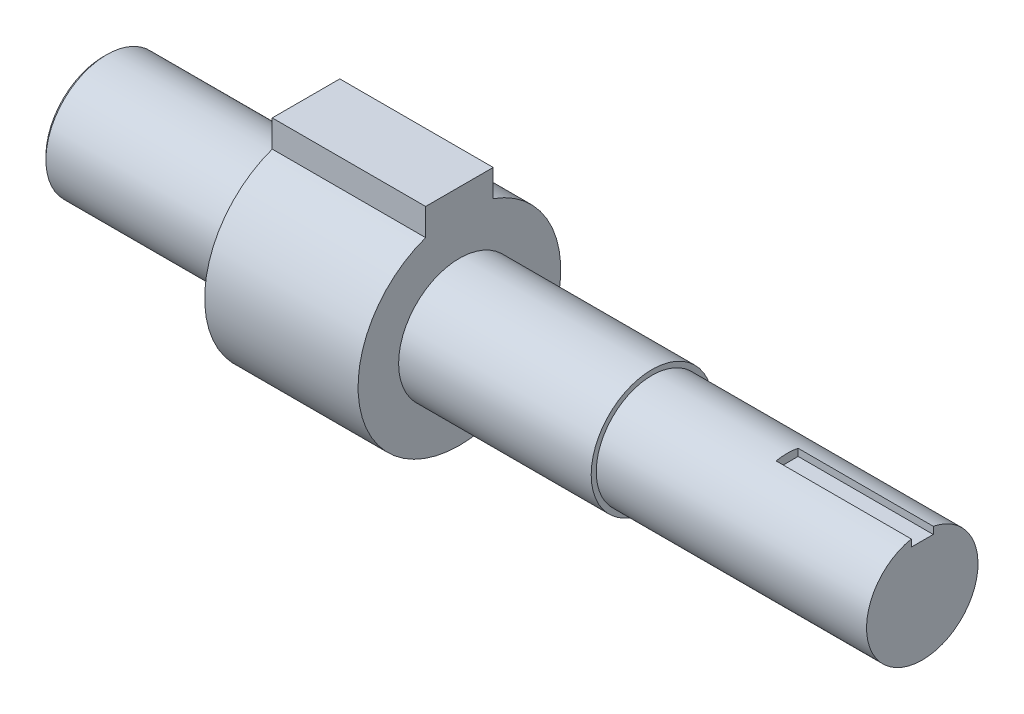
SolidWorks part; units mm, degrees
ref_plane "Front Plane" through (0, 0, 0) normal (0, 0, 1) x (1, 0, 0)
ref_plane "Top Plane" through (0, 0, 0) normal (0, 1, 0) x (1, 0, 0)
ref_plane "Right Plane" through (0, 0, 0) normal (1, 0, 0) x (0, 0, -1)
sketch "Sketch1" plane through (0, 0, 0) normal (0, 0, 1) x (1, 0, 0)
  line L1 (0, 0) -> (30, 0)
  line L2 (0, 0) -> (0, 9)
  line L3 (0, 9) -> (30, 9)
  line L4 (30, 0) -> (30, 9)
  dimension "D1" = 9
  dimension "D2" = 30
revolve "Revolve1" add sketch "Sketch1" angle 360 about L1
sketch "Sketch2" plane through (30, 0, 0) normal (1, 0, 0) x (0, 0, -1)
  line L0 (0, 0) -> (0, 13.3284) construction
  line L2 (5, 18.1421) -> (-5, 18.1421)
  line L3 (5, 18.1421) -> (5, 14.1421)
  line L5 (-5, 18.1421) -> (-5, 14.1421)
  line L6 (5, 18.1421) -> (0, 15) construction
  line L7 (0, 15) -> (-5, 18.1421) construction
  arc A0 (-5, 14.1421) -> (5, 14.1421) centre (0, 0) ccw
  point P4 (0, 15)
  dimension "D2" = 30
  dimension "D1" = 10
  dimension "D3" = 4
  dimension "D4" = 5
extrude "Boss-Extrude1" add sketch "Sketch2" along normal blind 22.7
sketch "Sketch3" plane through (52.7, 0, 0) normal (1, 0, 0) x (0, 0, -1)
  circle A0 centre (0, 0) radius 9 construction
  circle A1 centre (0, 0) radius 9
extrude "Boss-Extrude2" add sketch "Sketch3" along normal blind 28.5
sketch "Sketch4" plane through (81.2, 0, 0) normal (1, 0, 0) x (0, 0, -1)
  circle A0 centre (0, 0) radius 8.25
  dimension "D1" = 16.5
extrude "Boss-Extrude3" add sketch "Sketch4" along normal blind 40
sketch "Sketch5" plane through (121.2, 0, 0) normal (1, 0, 0) x (0, 0, -1)
  line L0 (0, 0) -> (0, 12.3861) construction
  line L2 (-1.625, 8.54) -> (1.625, 8.54)
  line L3 (-1.625, 8.54) -> (-1.625, 7.04)
  line L4 (-1.625, 7.04) -> (1.625, 7.04)
  line L5 (1.625, 8.54) -> (1.625, 7.04)
  line L6 (-1.625, 8.54) -> (1.625, 7.04) construction
  line L7 (-1.625, 7.04) -> (1.625, 8.54) construction
  point P3 (2.2063, 8.8083)
  dimension "D1" = 3.25
  dimension "D2" = 1.5
  dimension "D3" = 7.04
extrude "Cut-Extrude1" cut sketch "Sketch5" against normal blind 20
chamfer "Chamfer1" distance 0.5 angle 45 1 edges at (0, 0, 9)
